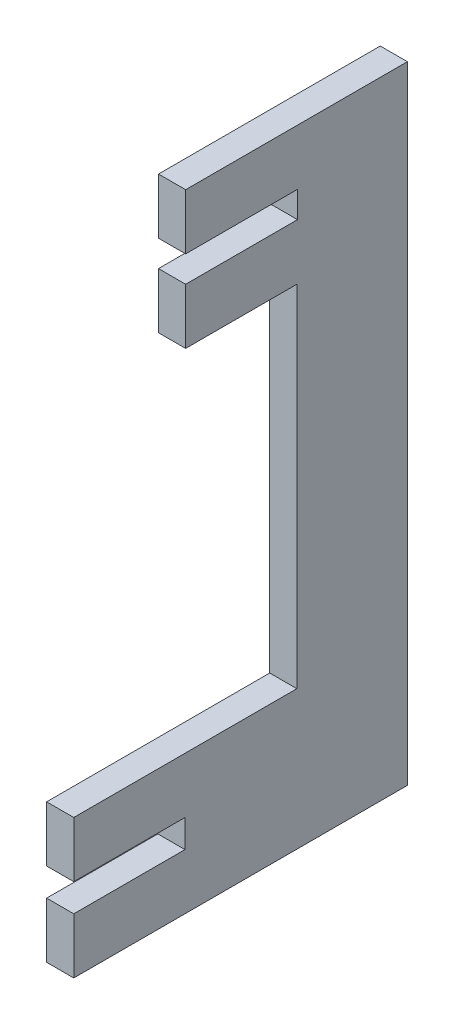
SolidWorks part; units mm, degrees
material "Corrugated Paper"
ref_plane "Front Plane" through (0, 0, 0) normal (0, 0, 1) x (1, 0, 0)
ref_plane "Top Plane" through (0, 0, 0) normal (0, 1, 0) x (1, 0, 0)
ref_plane "Right Plane" through (0, 0, 0) normal (1, 0, 0) x (0, 0, -1)
sketch "Sketch1" plane through (0, 0, 0) normal (1, 0, 0) x (0, 0, -1)
  line L0 (-12.7, -1.5875) -> (-12.7, -7.9375)
  line L1 (-12.7, 1.5875) -> (0, 1.5875)
  line L3 (-12.7, -1.5875) -> (0, -1.5875)
  line L4 (0, 1.5875) -> (0, -1.5875)
  line L5 (-12.7, -7.9375) -> (25.4, -7.9375)
  line L6 (-12.7, 1.5875) -> (-12.7, 7.9375)
  line L7 (-12.7, 7.9375) -> (12.7762, 7.9375)
  line L8 (25.4, -7.9375) -> (25.4, 63.6375)
  line L9 (12.7762, 7.9375) -> (12.7762, 47.9375)
  line L10 (12.7762, 47.9375) -> (0.0762, 47.9375)
  line L11 (25.4, 63.6375) -> (0.0762, 63.6375)
  line L12 (0.0762, 63.6375) -> (0.0762, 57.2875)
  line L13 (0.0762, 57.2875) -> (12.8524, 57.2875)
  line L14 (12.8524, 57.2875) -> (12.8524, 54.2875)
  line L15 (12.8524, 54.2875) -> (0.0762, 54.2875)
  line L16 (0.0762, 54.2875) -> (0.0762, 47.9375)
  line L17 (12.7762, 57.2875) -> (12.7762, 54.2875) construction
  dimension "D1" = 3.175
  dimension "D2" = 12.7
  dimension "D3" = 25.4
  dimension "D4" = 6.35
  dimension "D5" = 6.35
  dimension "D6" = 12.7762
  dimension "D7" = 40
  dimension "D8" = 3
  dimension "D9" = 12.7
  dimension "D10" = 6.35
  dimension "D11" = 0.0762
extrude "Boss-Extrude1" add sketch "Sketch1" along normal blind 3.0988
equation "\"rodThick\"= 0.085in"
equation "\"thick\"= 0.122in"
equation "\"clear\"= 0.003in"
equation "\"D1@Sketch1\"=\"thick\"+\"clear\""
equation "\"D6@Sketch1\"= 0.5 + \"clear\""
equation "\"D1@Boss-Extrude1\"=\"thick\""
equation "\"D11@Sketch1\"=\"clear\""
